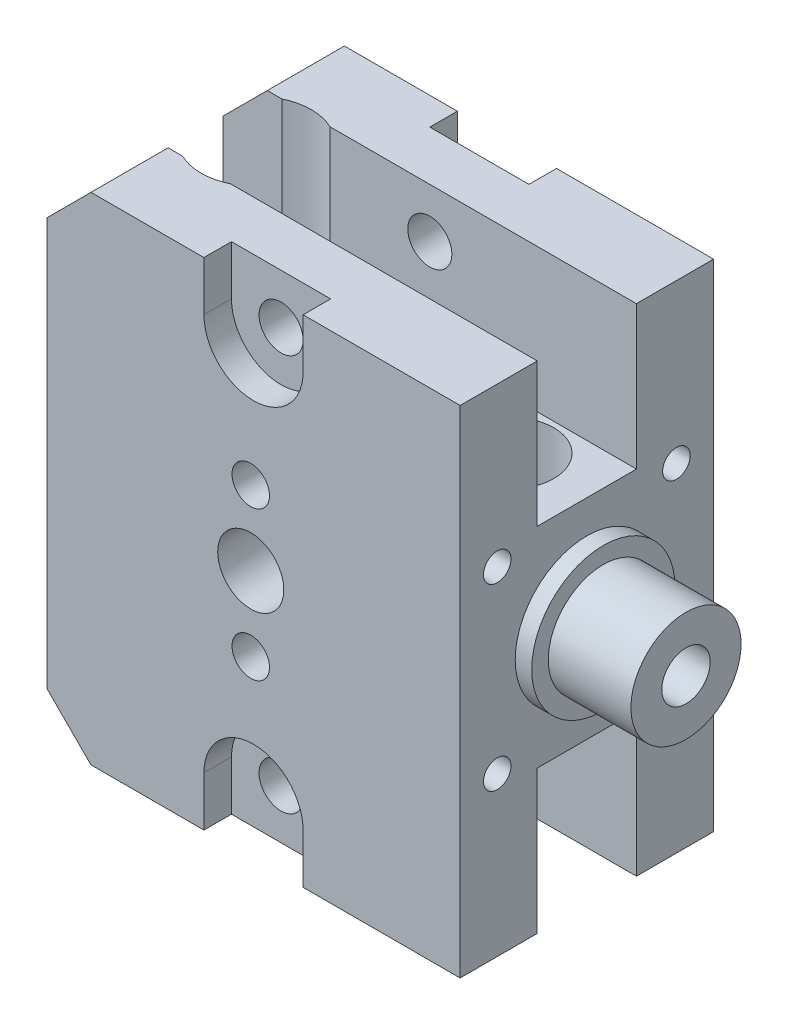
SolidWorks part; units mm, degrees
ref_plane "Front Plane" through (0, 0, 0) normal (0, 0, 1) x (1, 0, 0)
ref_plane "Top Plane" through (0, 0, 0) normal (0, 1, 0) x (1, 0, 0)
ref_plane "Right Plane" through (0, 0, 0) normal (1, 0, 0) x (0, 0, -1)
sketch "Sketch2" plane through (0, 0, 0) normal (0, 0, 1) x (1, 0, 0)
  line L0 (0, 0) -> (45.8143, 0) construction
  line L1 (38, -45) -> (-37, -45)
  line L2 (38, -45) -> (38, 45)
  line L3 (38, 45) -> (-37, 45)
  line L4 (-37, -45) -> (-37, 45)
  point P0 (0, 0)
  dimension "D1" = 75
  dimension "D2" = 90
  dimension "D3" = 38
extrude "Boss-Extrude1" add sketch "Sketch2" along normal mid plane 46
sketch "Sketch3" plane through (38, 0, 0) normal (1, 0, 0) x (0, 0, -1)
  line L0 (-23, -45) -> (23, -45) construction
  line L1 (-9, -19) -> (9, -19)
  line L2 (-9, -19) -> (-9, -45)
  line L3 (-9, -45) -> (9, -45)
  line L4 (9, -19) -> (9, -45)
  line L5 (0, 0) -> (0, -49.7646) construction
  line L6 (0, 0) -> (38.1899, 0) construction
  line L7 (9, 19) -> (9, 45)
  line L8 (-9, 45) -> (9, 45)
  line L9 (-9, 19) -> (-9, 45)
  line L10 (-9, 19) -> (9, 19)
  line L11 (-23, 45) -> (23, 45) construction
  dimension "D1" = 18
  dimension "D2" = 38
extrude "Cut-Extrude1" cut sketch "Sketch3" against normal through all
sketch "Sketch4" plane through (38, 0, 0) normal (1, 0, 0) x (0, 0, -1)
  circle A0 centre (0, 0) radius 10
  dimension "D1" = 20
extrude "Boss-Extrude2" add sketch "Sketch4" along normal blind 18
sketch "Sketch5" plane through (38, 0, 0) normal (1, 0, 0) x (0, 0, -1)
  circle A0 centre (0, 0) radius 13
  dimension "D1" = 26
extrude "Boss-Extrude3" add sketch "Sketch5" along normal blind 3
hole_wizard "Ø12.0 (12) Diameter Hole1" positions "Sketch7" profile "Sketch8" hole size "Ø12.0" standard "ISO" end condition through all
sketch "Sketch7" plane through (0, 0, -23) normal (0, 0, -1) x (-1, 0, 0)
  point P0 (0, 0)
sketch "Sketch8" plane through (0, 0, -23) normal (1, 0, 0) x (0, 1, 0)
  line L0 (0, 0) -> (0, 46)
  line L1 (0, 46) -> (6, 46)
  line L2 (6, 46) -> (6, 0)
  line L5 (6, 0) -> (0, 0)
  line L11 (0, -6.35) -> (0, 107.95) construction
  dimension "Thru Hole Dia." = 12
  dimension "Thru Hole Depth" = 46
sketch "Sketch9" plane through (0, 0, -23) normal (0, 0, -1) x (-1, 0, 0)
  line L0 (-0.5, -45) -> (-0.5, -36) construction
  line L1 (37, -45) -> (-38, -45) construction
  line L2 (-9.5, -45) -> (-9.5, -36)
  line L3 (8.5, -45) -> (8.5, -36)
  line L4 (25.3, 0) -> (-25.3, 0) construction
  line L5 (-0.5, 45) -> (-0.5, 36) construction
  line L6 (-9.5, 45) -> (-9.5, 36)
  line L7 (8.5, 45) -> (8.5, 36)
  arc A0 (-9.5, -45) -> (8.5, -45) centre (-0.5, -45) ccw
  arc A1 (8.5, -36) -> (-9.5, -36) centre (-0.5, -36) ccw
  arc A2 (-9.5, 45) -> (8.5, 45) centre (-0.5, 45) cw
  arc A3 (8.5, 36) -> (-9.5, 36) centre (-0.5, 36) cw
  point P4 (-0.5, -40.5)
  point P9 (8.5, -40.5)
  point P14 (-0.5, 40.5)
  dimension "D1" = 18
  dimension "D2" = 72
extrude "Cut-Extrude2" cut sketch "Sketch9" against normal blind 5
mirror "Mirror1" about plane through (0, 0, 0) normal (0, 0, 1) of "Cut-Extrude2"
hole_wizard "Ø8.0 (8) Diameter Hole1" positions "Sketch10" profile "Sketch11" hole size "Ø8.0" standard "ISO" end condition through all
sketch "Sketch10" plane through (0, 0, -18) normal (0, 0, -1) x (-1, 0, 0)
  point P0 (-0.5, -36)
  point P3 (-0.5, 36)
sketch "Sketch11" plane through (0.5, -36, -18) normal (1, 0, 0) x (0, 1, 0)
  line L0 (0, 0) -> (0, 41)
  line L1 (0, 41) -> (4, 41)
  line L2 (4, 41) -> (4, 0)
  line L5 (4, 0) -> (0, 0)
  line L11 (0, -6.35) -> (0, 107.95) construction
  dimension "Thru Hole Dia." = 8
  dimension "Thru Hole Depth" = 41
hole_wizard "M8 Tapped Hole1" positions "Sketch15" profile "Sketch16" tap size "M8" standard "ISO" end condition up to next
sketch "Sketch15" plane through (0, 0, -23) normal (0, 0, -1) x (-1, 0, 0)
  line L0 (0, 0) -> (26.8998, 0) construction
  point P0 (0, 13.5)
  point P2 (0, -13.5)
  dimension "D1" = 27
sketch "Sketch16" plane through (0, 13.5, -23) normal (1, 0, 0) x (0, 1, 0)
  line L0 (0, 0) -> (0, 46)
  line L1 (0, 46) -> (3.4, 46)
  line L2 (3.4, 46) -> (3.4, 0)
  line L5 (3.4, 0) -> (0, 0)
  line L11 (0, -6.35) -> (0, 107.95) construction
  dimension "Thru Tap Drill Dia." = 6.8
  dimension "Thru Tap Drill Depth" = 46
cosmetic thread "Hole Thread1" parameters "D2"=8
cosmetic thread "Hole Thread2" parameters "D2"=8
sketch "Sketch17" plane through (0, 45, 0) normal (0, 1, 0) x (1, 0, 0)
  line L0 (38, 9) -> (38, 23) construction
  circle A0 centre (24, 0) radius 8
  dimension "D2" = 16
  dimension "D1" = 14
extrude "Cut-Extrude3" cut sketch "Sketch17" against normal blind 38
mirror "Mirror2" about plane through (0, 0, 0) normal (0, 1, 0) of "Cut-Extrude3"
hole_wizard "Ø8.0 (8) Diameter Hole2" positions "Sketch18" profile "Sketch19" hole size "Ø8.0" standard "ISO" end condition up to next
sketch "Sketch18" plane through (0, 7, 0) normal (0, 1, 0) x (1, 0, 0)
  point P0 (24, 0)
sketch "Sketch19" plane through (24, 7, 0) normal (1, 0, 0) x (0, 0, 1)
  line L0 (0, 0) -> (0, 14)
  line L1 (0, 14) -> (4, 14)
  line L2 (4, 14) -> (4, 0)
  line L5 (4, 0) -> (0, 0)
  line L11 (0, -6.35) -> (0, 107.95) construction
  dimension "Thru Hole Dia." = 8
  dimension "Thru Hole Depth" = 14
chamfer "Chamfer1" distance 8 4 edges at (-37, -45, 16) (-37, -45, -16) (-37, 45, -16) (-37, 45, 16)
hole_wizard "G1/8 Tapped Hole1" positions "Sketch24" profile "Sketch25" tap size "G1/8" standard "ISO"
sketch "Sketch24" plane through (56, 0, 0) normal (1, 0, 0) x (0, 0, -1)
  point P0 (0, 0)
sketch "Sketch25" plane through (56, 0, 0) normal (0, 1, 0) x (0, 0, -1)
  line L0 (0, 0) -> (0, 16.6438)
  line L1 (0, 16.6438) -> (4.4, 14)
  line L2 (4.4, 14) -> (4.4, 0)
  line L5 (4.4, 0) -> (0, 0)
  line L10 (0, 16.6438) -> (-4.4, 14) construction
  line L11 (0, -6.35) -> (0, 107.95) construction
  dimension "Tap Drill Dia." = 8.8
  dimension "Tap Drill Depth" = 14
  dimension "Drill Angle" = 118
cosmetic thread "Hole Thread4" parameters "D1"=14, "D2"=9.728
hole_wizard "Ø2.0 (2) Diameter Hole1" positions "Sketch26" profile "Sketch27" hole size "Ø2.0" standard "ISO"
sketch "Sketch26" plane through (56, 0, 0) normal (1, 0, 0) x (0, 0, -1)
  point P0 (0, 0)
sketch "Sketch27" plane through (56, 0, 0) normal (0, 1, 0) x (0, 0, -1)
  line L0 (0, 0) -> (0, 28)
  line L1 (0, 28) -> (1, 28)
  line L2 (1, 28) -> (1, 0)
  line L5 (1, 0) -> (0, 0)
  line L11 (0, -6.35) -> (0, 107.95) construction
  dimension "Thru Hole Dia." = 2
  dimension "Thru Hole Depth" = 28
hole_wizard "M6 Tapped Hole1" positions "Sketch28" profile "Sketch29" tap size "M6" standard "ISO"
sketch "Sketch28" plane through (-37, 0, 0) normal (-1, 0, 0) x (0, 0, 1)
  point P0 (0, 0)
sketch "Sketch29" plane through (-37, 0, 0) normal (0, 1, 0) x (0, 0, 1)
  line L0 (0, 0) -> (0, 31)
  line L1 (0, 31) -> (2.5, 31)
  line L2 (2.5, 31) -> (2.5, 0)
  line L5 (2.5, 0) -> (0, 0)
  line L11 (0, -6.35) -> (0, 107.95) construction
  dimension "Thru Tap Drill Dia." = 5
  dimension "Thru Tap Drill Depth" = 31
cosmetic thread "Hole Thread5" parameters "D2"=6
hole_wizard "M6 Tapped Hole2" positions "Sketch33" profile "Sketch34" tap size "M6" standard "ISO"
sketch "Sketch33" plane through (38, 0, 0) normal (1, 0, 0) x (0, 0, -1)
  line L0 (0, 0) -> (-16.2635, 16.2635) construction
  point P0 (-16.2635, 16.2635)
  dimension "D1" = 23
  dimension "D2" = 45
sketch "Sketch34" plane through (38, 16.2635, 16.2635) normal (0, 1, 0) x (0, 0, -1)
  line L0 (0, 0) -> (0, 16.5022)
  line L1 (0, 16.5022) -> (2.5, 15)
  line L2 (2.5, 15) -> (2.5, 0)
  line L5 (2.5, 0) -> (0, 0)
  line L10 (0, 16.5022) -> (-2.5, 15) construction
  line L11 (0, -6.35) -> (0, 107.95) construction
  dimension "Tap Drill Dia." = 5
  dimension "Tap Drill Depth" = 15
  dimension "Drill Angle" = 118
cosmetic thread "Hole Thread6" parameters "D1"=12, "D2"=6
pattern_circular "CirPattern1" count 4 over 360 about axis through (0, 0, 0) along (1, 0, 0) of "M6 Tapped Hole2"
cosmetic thread "Hole Thread7" parameters "D1"=12, "D2"=6
cosmetic thread "Hole Thread8" parameters "D1"=12, "D2"=6
cosmetic thread "Hole Thread9" parameters "D1"=12, "D2"=6
sketch "Sketch36" plane through (0, -45, 0) normal (0, -1, 0) x (1, 0, 0)
  circle A0 centre (-22, 0) radius 10
  circle A1 centre (24, 0) radius 8 construction
  dimension "D2" = 20
  dimension "D1" = 46
extrude "Cut-Extrude5" cut sketch "Sketch36" against normal blind 38
mirror "Mirror4" about plane through (0, 0, 0) normal (0, 1, 0) of "Cut-Extrude5"
hole_wizard "M8 Tapped Hole2" positions "Sketch37" profile "Sketch38" tap size "M8" standard "ISO" end condition through all
sketch "Sketch37" plane through (0, -7, 0) normal (0, -1, 0) x (-1, 0, 0)
  point P0 (22, 0)
sketch "Sketch38" plane through (-22, -7, 0) normal (1, 0, 0) x (0, 0, -1)
  line L0 (0, 0) -> (0, 52)
  line L1 (0, 52) -> (3.4, 52)
  line L2 (3.4, 52) -> (3.4, 0.625)
  line L3 (3.4, 0.625) -> (4.025, 0)
  line L5 (4.025, 0) -> (0, 0)
  line L6 (-3.4, 0.625) -> (-4.025, 0) construction
  line L11 (0, -6.35) -> (0, 107.95) construction
  dimension "Thru Tap Drill Dia." = 6.8
  dimension "Thru Tap Drill Depth" = 52
  dimension "Near C'Sink Dia." = 8.05
  dimension "Near C'Sink Angle" = 90
cosmetic thread "Hole Thread10" parameters "D2"=8
